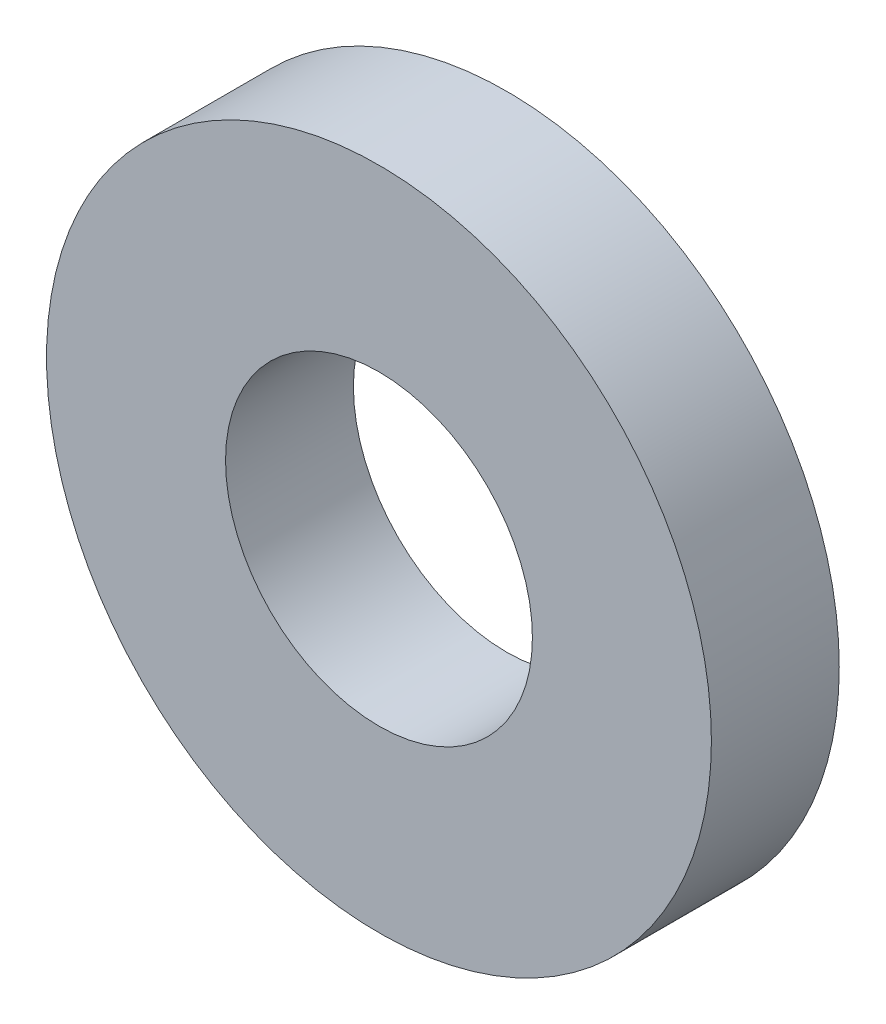
SolidWorks part; units mm, degrees
ref_plane "Front Plane" through (0, 0, 0) normal (0, 0, 1) x (1, 0, 0)
ref_plane "Top Plane" through (0, 0, 0) normal (0, 1, 0) x (1, 0, 0)
ref_plane "Right Plane" through (0, 0, 0) normal (1, 0, 0) x (0, 0, -1)
sketch "Sketch1" plane through (0, 0, 0) normal (0, 0, 1) x (1, 0, 0)
  circle A0 centre (0, 0) radius 6.5
  circle A1 centre (0, 0) radius 3
  dimension "D1" = 6
  dimension "D2" = 13
extrude "Boss-Extrude1" add sketch "Sketch1" along normal blind 2.5
equation "\"roller_radius\"= 6.5"
equation "\"eccentricity\"= \"roller_radius\" * 0.325"
equation "\"outer_radius\"= 40"
equation "\"eccentric_shaft_radius\"= 16"
equation "\"rotor_width\"= 10"
equation "\"housing_depth\"= 40"
equation "\"bottom_depth\"= 5"
equation "\"roller_bearing_OD\"= \"roller_radius\" * 2"
equation "\"roller_bearing_ID\"= 6"
equation "\"eccentric_bearing_ID\"= 6"
equation "\"eccentric_bearing_OD\"= 15"
equation "\"roller_bearing_height\"= 5"
equation "\"eccentric_bearing_height\"= 5"
equation "\"bottom_bearing_ID\"= 15"
equation "\"bottom_bearing_OD\"= 32"
equation "\"bottom_bearing_height\"= 9"
equation "\"distance_to_output_rotor_holes\"= 20"
equation "\"D1@Sketch1\"=\"roller_bearing_ID\""
equation "\"D2@Sketch1\"=\"roller_bearing_OD\""
equation "\"output_bearing_ID\" = 25"
equation "\"output_bearing_OD\" = 37"
equation "\"output_bearing_height\" = 7"
equation "\"number_of_rollers\" = 15"
equation "\"housing_height\" = 27"
equation "\"spacer_1\" = 7"
equation "\"spacer_2\" = 2.5"
equation "\"spacer_3\" = 7.5"
equation "\"roller_pin_depth\" = 5"
equation "\"D1@Boss-Extrude1\"=\"spacer_2\""
